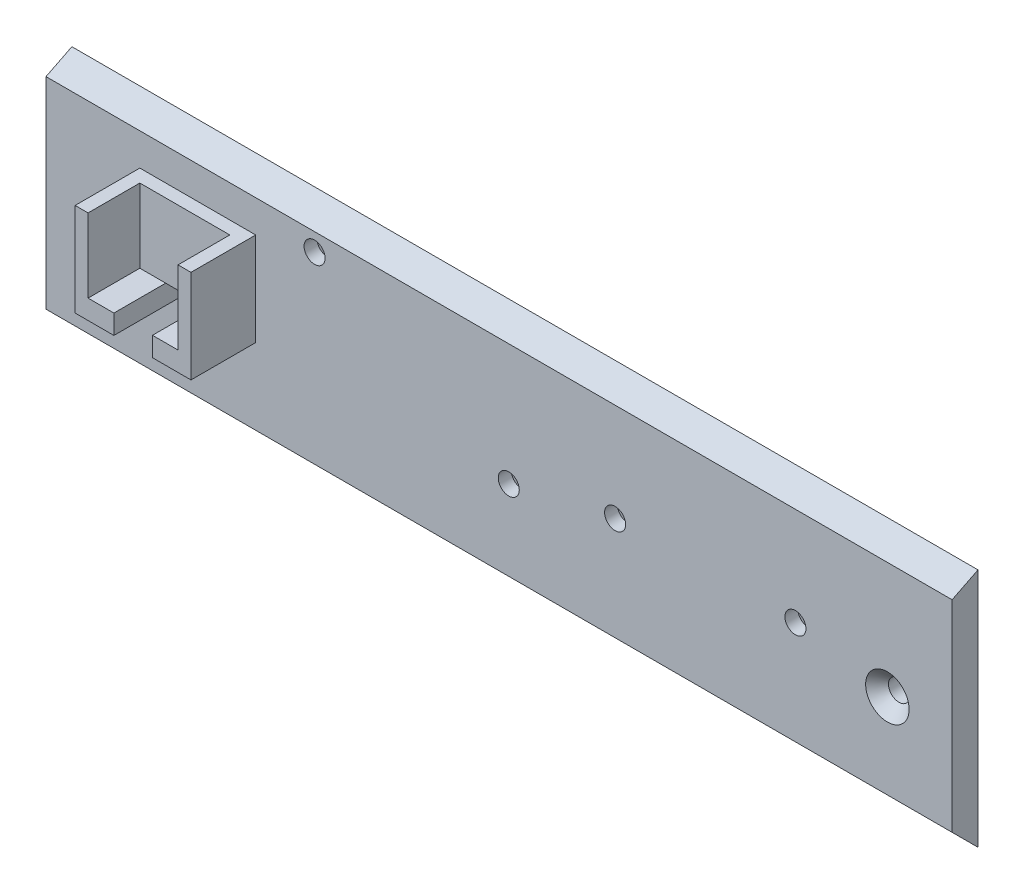
SolidWorks part; units mm, degrees
ref_plane "Alzado" through (0, 0, 0) normal (0, 0, 1) x (1, 0, 0)
ref_plane "Planta" through (0, 0, 0) normal (0, 1, 0) x (1, 0, 0)
ref_plane "Vista lateral" through (0, 0, 0) normal (1, 0, 0) x (0, 0, -1)
sketch "Croquis1" plane through (0, 0, 0) normal (0, 0, 1) x (1, 0, 0)
  line L5 (132.679, -67.2841) -> (-7.321, -67.2841)
  line L6 (132.679, -67.2841) -> (132.679, -104.4091)
  line L7 (132.679, -104.4091) -> (-7.321, -104.4091)
  line L8 (-7.321, -67.2841) -> (-7.321, -104.4091)
  circle A0 centre (122.679, -87.2841) radius 1.625
  circle A1 centre (2.679, -87.2841) radius 1.625
  dimension "D5" = 7.321
  dimension "D1" = 3.25
  dimension "D2" = 2.679
  dimension "D3" = 122.679
  dimension "D4" = 132.679
  dimension "D6" = 67.2841
  dimension "D7" = 87.2841
  dimension "D8" = 104.4091
extrude "Saliente-Extruir1" add sketch "Croquis1" along normal blind 4
sketch "Croquis2" plane through (0, 0, 4) normal (0, 0, 1) x (1, 0, 0)
  line L0 (-7.321, -67.2841) -> (-7.321, -104.4091) construction
  line L1 (132.679, -67.2841) -> (-7.321, -67.2841) construction
  circle A0 centre (2.679, -87.2841) radius 3.36
  circle A1 centre (122.679, -87.2841) radius 3.36
  dimension "D1" = 6.7199
  dimension "D2" = 10
  dimension "D3" = 130
  dimension "D4" = 20
extrude "Cortar-Extruir1" cut sketch "Croquis2" against normal blind 1.8 draft 44
sketch "Croquis3" plane through (0, 0, 4) normal (0, 0, 1) x (1, 0, 0)
  line L1 (132.679, -104.4091) -> (132.679, -67.2841) construction
  circle A0 centre (80.609, -84.4491) radius 1.625
  circle A1 centre (108.469, -84.4541) radius 1.625
  circle A4 centre (34.179, -72.0341) radius 1.625
  circle A5 centre (64.179, -88.0341) radius 1.625
  dimension "D1" = 3.25
  dimension "D2" = 24.21
  dimension "D3" = 52.07
  dimension "D4" = 19.955
  dimension "D5" = 19.96
extrude "Cortar-Extruir2" cut sketch "Croquis3" against normal up to vertex (4 mm away)
sketch "Croquis4" plane through (0, 0, 4) normal (0, 0, 1) x (1, 0, 0)
  line L0 (13.171, -85.6743) -> (13.171, -88.6743)
  line L1 (19.129, -85.6743) -> (19.1388, -88.6743)
  line L2 (9.679, -84.6743) -> (9.179, -84.6743) construction
  line L3 (22.579, -84.6743) -> (23.079, -84.6743) construction
  line L4 (9.179, -85.6743) -> (9.179, -74.2743)
  line L5 (9.179, -85.6743) -> (7.179, -85.6743) construction
  line L6 (9.179, -85.6743) -> (13.171, -85.6743)
  line L7 (19.129, -85.6743) -> (23.079, -85.6743)
  line L8 (23.079, -85.6743) -> (23.079, -74.2743)
  line L9 (9.179, -85.6743) -> (9.179, -88.6743) construction
  line L10 (7.179, -88.6743) -> (7.179, -74.2743)
  line L11 (7.179, -74.2743) -> (9.179, -74.2743)
  line L12 (23.079, -74.2743) -> (25.079, -74.2743)
  line L13 (25.079, -74.2743) -> (25.079, -88.6743)
  line L14 (25.079, -88.6743) -> (19.1388, -88.6743)
  line L16 (7.179, -88.6743) -> (13.171, -88.6743)
  circle A1 centre (2.679, -87.2841) radius 3.36 construction
  dimension "D1" = 4.5
  dimension "D2" = 6.5
  dimension "D3" = 10.492
  dimension "D4" = 16.45
  dimension "D5" = 16.4598
  dimension "D6" = 20.4
  dimension "D7" = 1.6098
  dimension "D8" = 2.6098
  dimension "D9" = 13.0098
  dimension "D10" = 1.3902
extrude "Saliente-Extruir2" add sketch "Croquis4" along normal blind 10
sketch "Croquis6" plane through (0, 0, 4) normal (0, 0, 1) x (1, 0, 0)
  line L0 (9.179, -85.6743) -> (9.179, -74.2743) construction
  line L1 (9.179, -74.2743) -> (23.079, -74.2743)
  line L2 (9.179, -74.2743) -> (9.179, -85.6743)
  line L3 (9.179, -85.6743) -> (23.079, -85.6743)
  line L4 (23.079, -74.2743) -> (23.079, -85.6743)
  line L5 (23.079, -85.6743) -> (19.129, -85.6743) construction
  line L6 (7.179, -74.2743) -> (7.179, -88.6743) construction
  line L7 (7.179, -88.6743) -> (13.171, -88.6743) construction
  dimension "D1" = 15.9
  dimension "D2" = 14.4
extrude "Saliente-Extruir4" add sketch "Croquis6" along normal blind 2
sketch "Croquis8" plane through (0, 0, 0) normal (0, 0, -1) x (-1, 0, 0)
  line L1 (-105.299, -84.4541) -> (-106.884, -81.7088)
  line L2 (-106.884, -81.7088) -> (-110.054, -81.7088)
  line L3 (-110.054, -81.7088) -> (-111.639, -84.4541)
  line L4 (-111.639, -84.4541) -> (-110.054, -87.1994)
  line L5 (-110.054, -87.1994) -> (-106.884, -87.1994)
  line L6 (-106.884, -87.1994) -> (-105.299, -84.4541)
  line L7 (-61.009, -88.0341) -> (-62.594, -85.2888)
  line L8 (-62.594, -85.2888) -> (-65.764, -85.2888)
  line L9 (-65.764, -85.2888) -> (-67.349, -88.0341)
  line L10 (-67.349, -88.0341) -> (-65.764, -90.7794)
  line L11 (-65.764, -90.7794) -> (-62.594, -90.7794)
  line L12 (-62.594, -90.7794) -> (-61.009, -88.0341)
  line L13 (-77.439, -84.4491) -> (-79.024, -81.7038)
  line L14 (-79.024, -81.7038) -> (-82.194, -81.7038)
  line L15 (-82.194, -81.7038) -> (-83.779, -84.4491)
  line L16 (-83.779, -84.4491) -> (-82.194, -87.1944)
  line L17 (-82.194, -87.1944) -> (-79.024, -87.1944)
  line L18 (-79.024, -87.1944) -> (-77.439, -84.4491)
  line L19 (-31.009, -72.0341) -> (-32.594, -69.2888)
  line L20 (-32.594, -69.2888) -> (-35.764, -69.2888)
  line L21 (-35.764, -69.2888) -> (-37.349, -72.0341)
  line L22 (-37.349, -72.0341) -> (-35.764, -74.7794)
  line L23 (-35.764, -74.7794) -> (-32.594, -74.7794)
  line L24 (-32.594, -74.7794) -> (-31.009, -72.0341)
  circle A0 centre (-108.469, -84.4541) radius 2.7453 construction
  circle A1 centre (-64.179, -88.0341) radius 2.7453 construction
  circle A2 centre (-80.609, -84.4491) radius 2.7453 construction
  circle A3 centre (-34.179, -72.0341) radius 2.7453 construction
  dimension "D1" = 5.4906
extrude "Cortar-Extruir3" cut sketch "Croquis8" against normal blind 2
sketch "Croquis9" plane through (-7.321, 0, 0) normal (-1, 0, 0) x (0, 0, 1)
  line L0 (4, -69.2841) -> (4, -100.4091) construction
  line L1 (4, -104.4091) -> (0, -104.4091)
  line L2 (4, -104.4091) -> (4, -100.4091)
  line L5 (0, -104.4091) -> (4, -100.4091)
  line L7 (4, -104.4091) -> (0, -104.4091) construction
  line L9 (0, -67.2841) -> (4, -67.2841)
  line L12 (4, -67.2841) -> (4, -69.2841)
  line L13 (4, -69.2841) -> (0, -67.2841)
  line L14 (0, -67.2841) -> (0, -104.4091) construction
  dimension "D1" = 4
  dimension "D2" = 4
  dimension "D3" = 35.125
  dimension "D4" = 37.125
extrude "Cortar-Extruir4" cut sketch "Croquis9" against normal up to vertex
